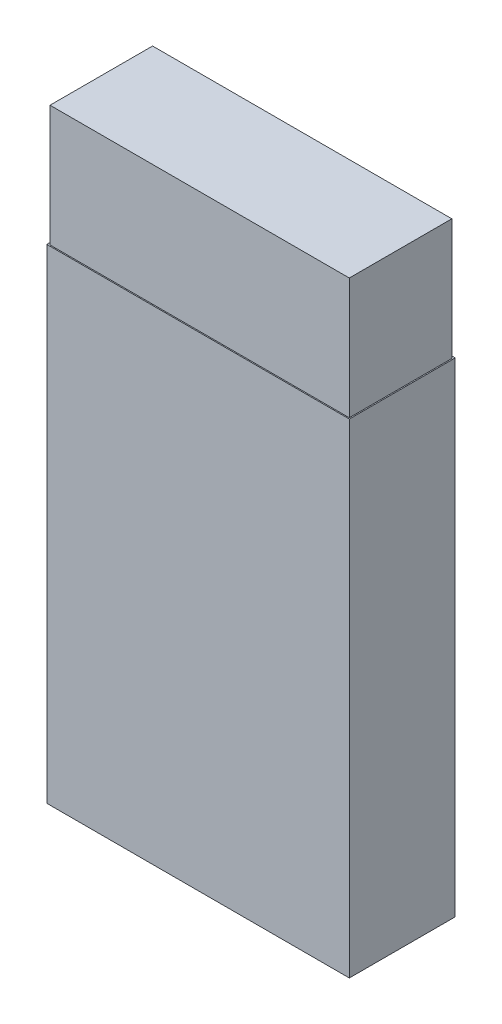
SolidWorks part; units mm, degrees
ref_plane "Front Plane" through (0, 0, 0) normal (0, 0, 1) x (1, 0, 0)
ref_plane "Top Plane" through (0, 0, 0) normal (0, 1, 0) x (1, 0, 0)
ref_plane "Right Plane" through (0, 0, 0) normal (1, 0, 0) x (0, 0, -1)
sketch "Sketch1" plane through (0, 0, 0) normal (0, 0, 1) x (1, 0, 0)
  line L1 (-8.1395, 11.9302) -> (1.8605, 11.9302)
  line L2 (-8.1395, 11.9302) -> (-8.1395, -4.0698)
  line L3 (-8.1395, -4.0698) -> (1.8605, -4.0698)
  line L4 (1.8605, 11.9302) -> (1.8605, -4.0698)
  line L5 (-8.1395, 11.9302) -> (1.8605, -4.0698) construction
  line L6 (-8.1395, -4.0698) -> (1.8605, 11.9302) construction
  point P0 (-3.1395, 3.9302)
  dimension "D1" = 10
  dimension "D2" = 16
extrude "Boss-Extrude1" add sketch "Sketch1" along normal blind 3.5
sketch "Sketch3" plane through (0, 11.9302, 0) normal (0, 1, 0) x (1, 0, 0)
  line L1 (-8.0686, -0.0741) -> (1.8228, -0.0741)
  line L2 (-8.0686, -0.0741) -> (-8.0686, -3.4638)
  line L3 (-8.0686, -3.4638) -> (1.8228, -3.4638)
  line L4 (1.8228, -0.0741) -> (1.8228, -3.4638)
  line L5 (-8.0686, -0.0741) -> (1.8228, -3.4638) construction
  line L6 (-8.0686, -3.4638) -> (1.8228, -0.0741) construction
  point P4 (-3.1229, -1.7689)
extrude "Boss-Extrude4" add sketch "Sketch3" along normal blind 4
